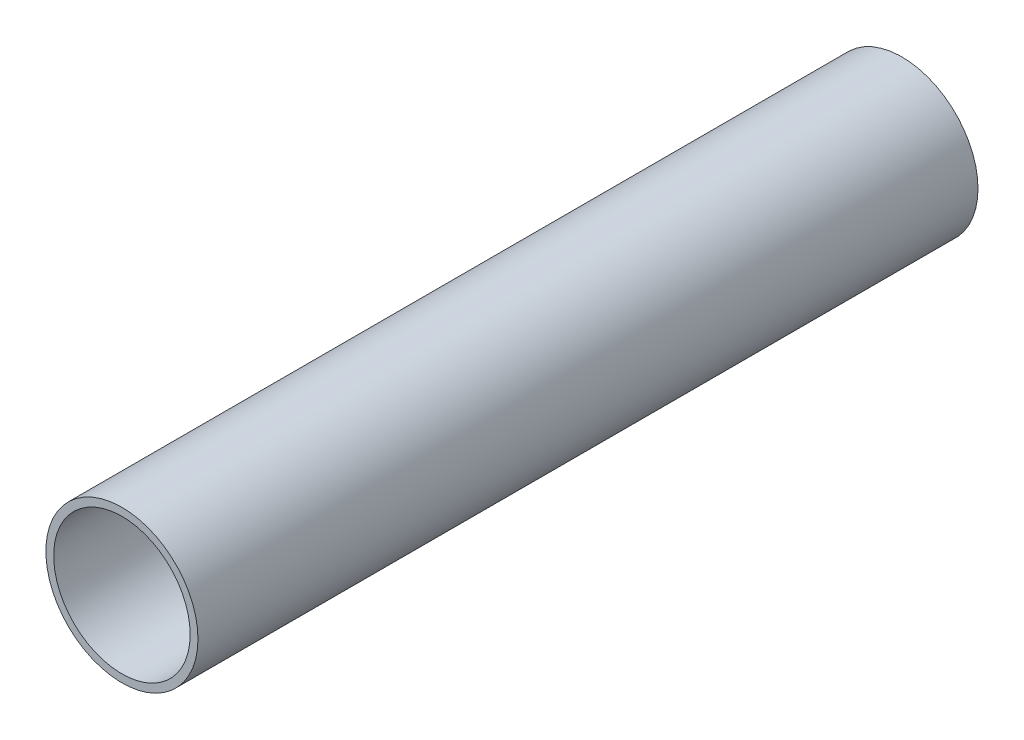
SolidWorks part; units mm, degrees
ref_plane "Front Plane" through (0, 0, 0) normal (0, 0, 1) x (1, 0, 0)
ref_plane "Top Plane" through (0, 0, 0) normal (0, 1, 0) x (1, 0, 0)
ref_plane "Right Plane" through (0, 0, 0) normal (1, 0, 0) x (0, 0, -1)
sketch "Sketch1" plane through (0, 0, 0) normal (0, 0, 1) x (1, 0, 0)
  circle A0 centre (0, 0) radius 1.75
  circle A1 centre (0, 0) radius 1.95
  dimension "D1" = 3.9
  dimension "D2" = 0.2
extrude "Boss-Extrude1" add sketch "Sketch1" along normal blind 20
